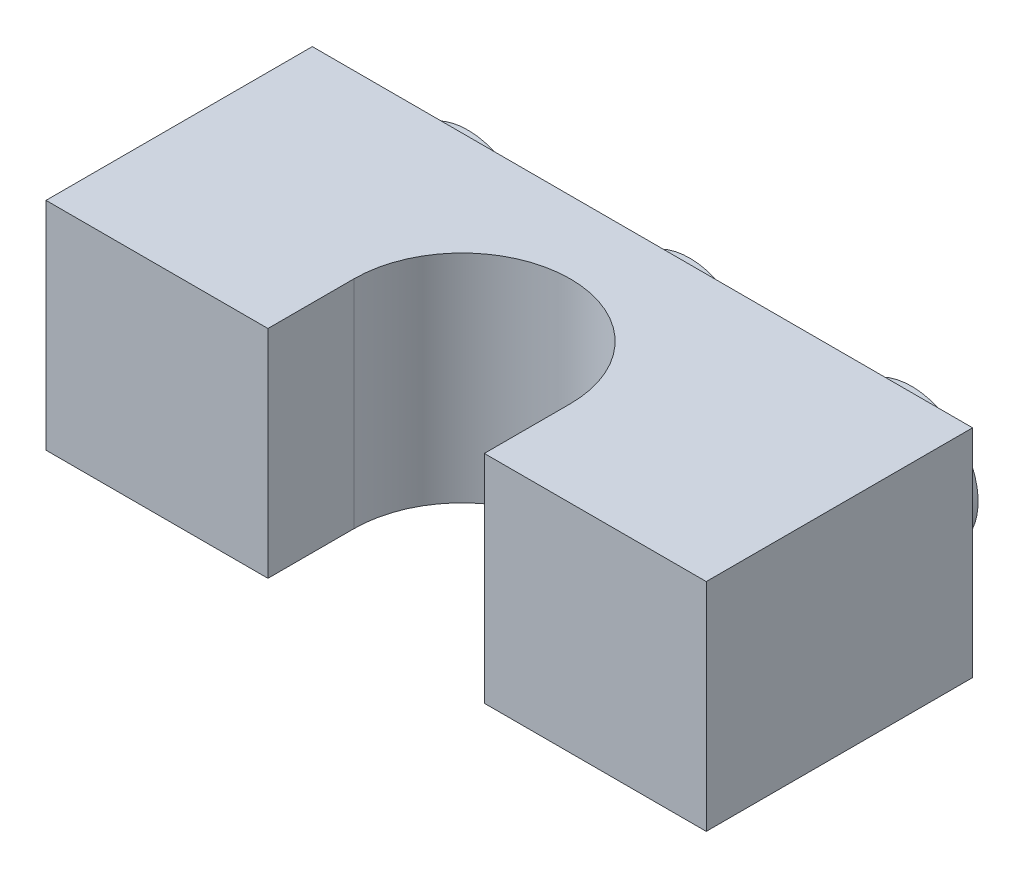
SolidWorks part; units mm, degrees
ref_plane "Спереди" through (0, 0, 0) normal (0, 0, 1) x (1, 0, 0)
ref_plane "Сверху" through (0, 0, 0) normal (0, 1, 0) x (1, 0, 0)
ref_plane "Справа" through (0, 0, 0) normal (1, 0, 0) x (0, 0, -1)
sketch "Эскиз1" plane through (0, 0, 0) normal (0, 0, 1) x (1, 0, 0)
  line L1 (-11.9, -3.9) -> (11.9, -3.9)
  line L2 (-11.9, -3.9) -> (-11.9, 3.9)
  line L3 (-11.9, 3.9) -> (11.9, 3.9)
  line L4 (11.9, -3.9) -> (11.9, 3.9)
  line L5 (-11.9, -3.9) -> (11.9, 3.9) construction
  line L6 (-11.9, 3.9) -> (11.9, -3.9) construction
  point P0 (0, 0)
  dimension "D1" = 23.8
  dimension "D2" = 7.8
extrude "Бобышка-Вытянуть1" add sketch "Эскиз1" along normal blind 9.6
sketch "Эскиз2" plane through (0, 0, 0) normal (0, 0, -1) x (-1, 0, 0)
  circle A0 centre (0, 0) radius 2.4
  circle A1 centre (8, 0) radius 2.4
  circle A2 centre (-8, 0) radius 2.4
  dimension "D1" = 8
  dimension "D2" = 8
extrude "Бобышка-Вытянуть2" add sketch "Эскиз2" along normal blind 1.7
sketch "Эскиз3" plane through (0, 3.9, 0) normal (0, 1, 0) x (1, 0, 0)
  line L0 (11.9, -9.6) -> (-11.9, -9.6) construction
  line L1 (-3.9, -16.6) -> (3.9, -16.6)
  line L2 (-3.9, -16.6) -> (-3.9, -6.5)
  line L4 (3.9, -16.6) -> (3.9, -6.5)
  line L5 (-0.4323, -10.376) -> (0, -9.6) construction
  line L7 (0, -2.6) -> (0, -9.6) construction
  line L8 (0, -9.6) -> (0.4323, -10.376) construction
  arc A0 (3.9, -6.5) -> (-3.9, -6.5) centre (0, -6.5) ccw
  point P0 (0, -9.6)
extrude "Вырез-Вытянуть1" cut sketch "Эскиз3" against normal through all
